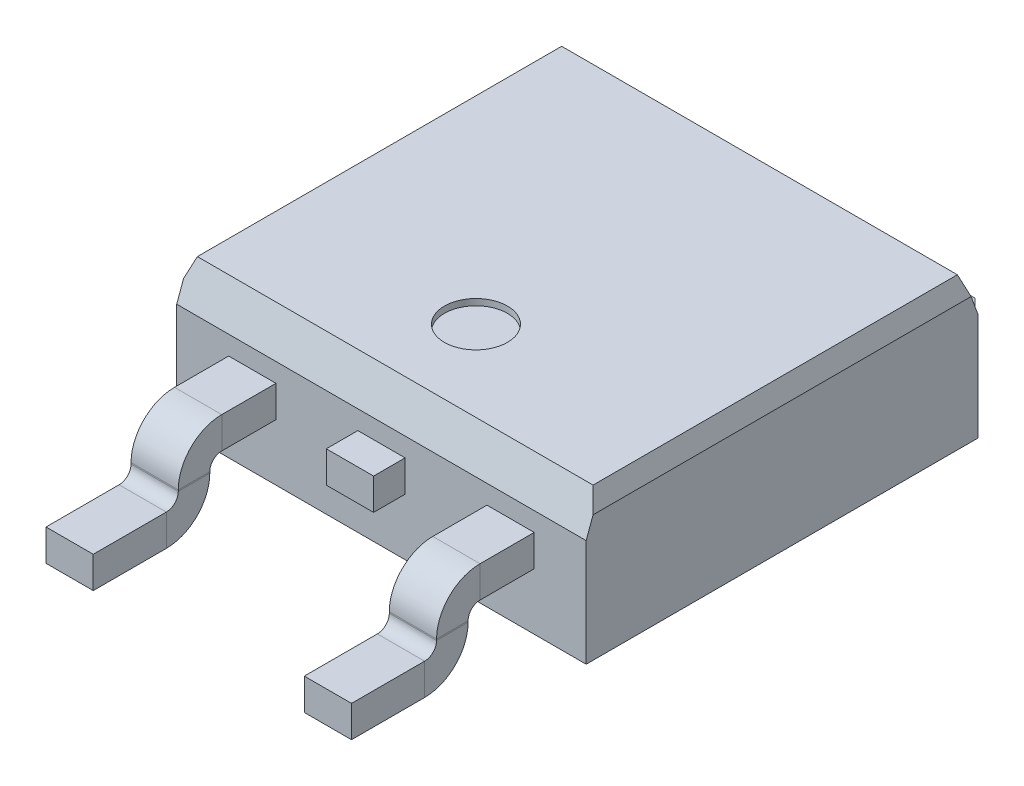
SolidWorks part; units mm, degrees
ref_plane "Front Plane" through (0, 0, 0) normal (0, 0, 1) x (1, 0, 0)
ref_plane "Top Plane" through (0, 0, 0) normal (0, 1, 0) x (1, 0, 0)
ref_plane "Right Plane" through (0, 0, 0) normal (1, 0, 0) x (0, 0, -1)
sketch "Sketch1" plane through (0, 0, 0) normal (0, 1, 0) x (1, 0, 0)
  line L1 (0, 0) -> (6.5, 0)
  line L2 (0, 0) -> (0, 6.22)
  line L3 (0, 6.22) -> (6.5, 6.22)
  line L4 (6.5, 0) -> (6.5, 6.22)
  dimension "D1" = 6.5
  dimension "D2" = 6.22
extrude "Boss-Extrude1" add sketch "Sketch1" along normal blind 2.3
sketch "Sketch2" plane through (0, 2.3, 0) normal (0, 1, 0) x (1, 0, 0)
  line L0 (0, 0) -> (6.5, 0) construction
  circle A0 centre (3.25, 1.5) radius 0.5
  dimension "D1" = 1
  dimension "D2" = 1.5
extrude "Cut-Extrude1" cut sketch "Sketch2" against normal blind 0.1
sketch "Sketch3" plane through (0, 0, -6.22) normal (0, 0, -1) x (-1, 0, 0)
  line L0 (-6.5, 0) -> (0, 0) construction
  line L1 (-5.95, 0) -> (-0.55, 0)
  line L2 (-5.95, 0) -> (-5.95, 0.9)
  line L3 (-5.95, 0.9) -> (-0.55, 0.9)
  line L4 (-0.55, 0) -> (-0.55, 0.9)
  line L5 (-6.5, 2.3) -> (-6.5, 0) construction
  dimension "D1" = 5.4
  dimension "D2" = 0.55
  dimension "D3" = 0.9
extrude "Boss-Extrude2" add sketch "Sketch3" along normal blind 1
chamfer "Chamfer2" distance 0.5 angle 45 2 edges at (5.95, 0.45, -7.22) (0.55, 0.45, -7.22)
sketch "Sketch5" plane through (0, 0, 0) normal (0, 0, 1) x (1, 0, 0)
  line L0 (0, 0) -> (6.5, 0) construction
  line L1 (0.825, 1.4) -> (1.575, 1.4)
  line L2 (0.825, 1.4) -> (0.825, 0.9)
  line L3 (0.825, 0.9) -> (1.575, 0.9)
  line L4 (1.575, 1.4) -> (1.575, 0.9)
  line L6 (0, 2.3) -> (0, 0) construction
  line L10 (4.925, 1.4) -> (5.675, 1.4)
  line L11 (4.925, 1.4) -> (4.925, 0.9)
  line L12 (4.925, 0.9) -> (5.675, 0.9)
  line L13 (5.675, 1.4) -> (5.675, 0.9)
  line L14 (2.875, 1.4) -> (3.625, 1.4) [skipped]
  line L15 (2.875, 1.4) -> (2.875, 0.9) [skipped]
  line L16 (2.875, 0.9) -> (3.625, 0.9) [skipped]
  line L17 (3.625, 1.4) -> (3.625, 0.9) [skipped]
  dimension "D1" = 0.75
  dimension "D2" = 0.5
  dimension "D3" = 0.9
  dimension "D4" = 0.825
  dimension "D5" = 3
ref_plane "Plane1" through (1.2, 0, 0) normal (1, 0, 0) x (0, 0, -1)
sketch "Sketch8" plane through (1.2, 0, 0) normal (1, 0, 0) x (0, 0, -1)
  line L0 (-1.3002, 0.69) -> (-1.3002, 0.71)
  line L1 (-0.8602, 1.15) -> (0, 1.15)
  line L2 (-1.7402, 0.25) -> (-2.9002, 0.25)
  arc A0 (-1.3002, 0.69) -> (-1.7402, 0.25) centre (-1.7402, 0.69) cw
  arc A1 (-1.3002, 0.71) -> (-0.8602, 1.15) centre (-0.8602, 0.71) cw
  point P7 (-1.3002, 0.25)
  point P10 (-1.3002, 1.15)
  dimension "D4" = 0.44
  dimension "D1" = 0.9
  dimension "D2" = 1.3002
  dimension "D3" = 1.6
sweep "Sweep2" add profiles "Sketch5" path "Sketch8"
sketch "Sketch10" plane through (0, 0, 0) normal (0, 0, 1) x (1, 0, 0)
  line L0 (1.575, 0.9) -> (1.575, 1.4) construction
  line L1 (2.875, 0.9) -> (3.625, 0.9)
  line L2 (2.875, 0.9) -> (2.875, 1.4)
  line L3 (2.875, 1.4) -> (3.625, 1.4)
  line L4 (3.625, 0.9) -> (3.625, 1.4)
  dimension "D1" = 0.75
  dimension "D2" = 0.5
  dimension "D3" = 1.3
extrude "Boss-Extrude3" add sketch "Sketch10" along normal blind 0.5
chamfer "Chamfer3" distance 0.6 angle 20 2 edges at (3.25, 2.3, -6.22) (3.25, 2.3, 0)
chamfer "Chamfer4" distance 0.3 angle 20 2 edges at (6.5, 2.3, -3.11) (0, 2.3, -3.11)
